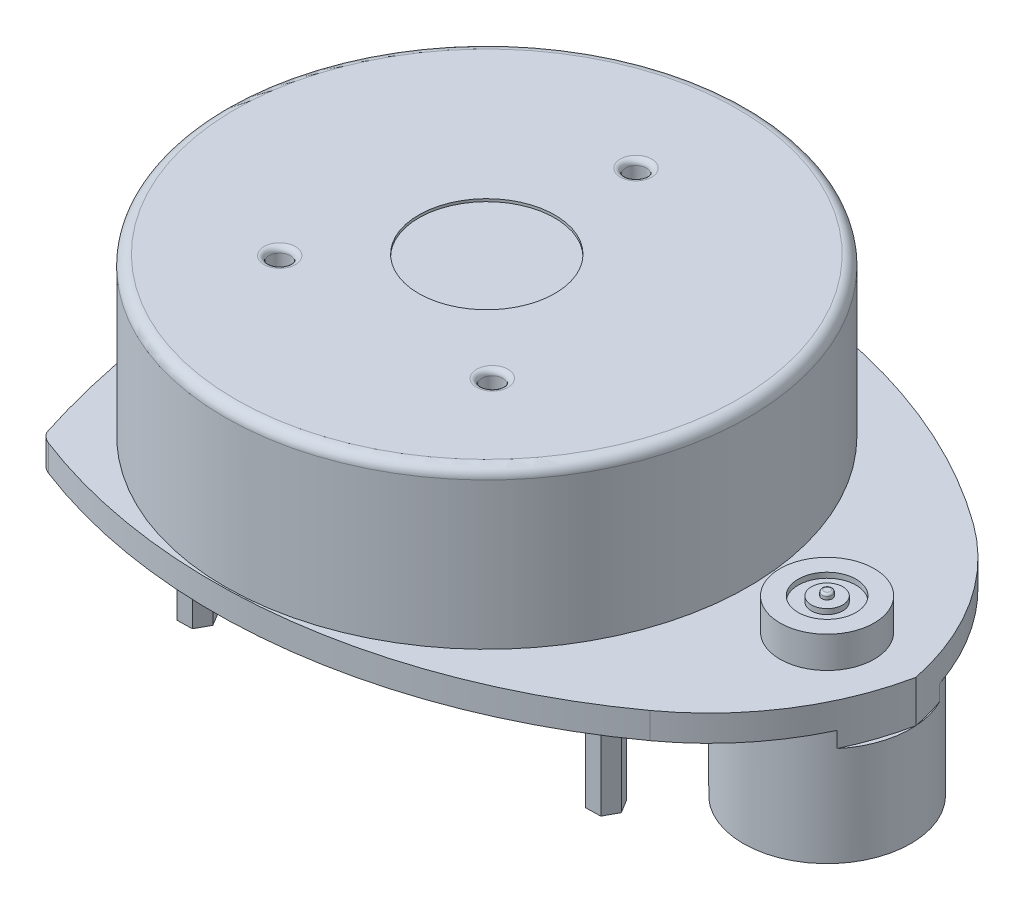
SolidWorks part; units mm, degrees
ref_plane "Спереди" through (0, 0, 0) normal (0, 0, 1) x (1, 0, 0)
ref_plane "Сверху" through (0, 0, 0) normal (0, 1, 0) x (1, 0, 0)
ref_plane "Справа" through (0, 0, 0) normal (1, 0, 0) x (0, 0, -1)
sketch "Эскиз1" plane through (0, 0, 0) normal (0, 1, 0) x (1, 0, 0)
  line L1 (-65, 55) -> (65, 55)
  line L2 (-65, 55) -> (-65, -55)
  line L3 (-65, -55) -> (65, -55)
  line L4 (65, 55) -> (65, -55)
  line L5 (-65, 55) -> (65, -55) construction
  line L6 (-65, -55) -> (65, 55) construction
  point P0 (0, 0)
  dimension "D1" = 130
  dimension "D2" = 110
extrude "Бобышка-Вытянуть1" add sketch "Эскиз1" along normal blind 5
sketch "Эскиз2" plane through (0, 5, 0) normal (0, 1, 0) x (1, 0, 0)
  line L0 (-65, 55) -> (-65, -55) construction
  circle A0 centre (-15, 0) radius 50
  point P2 (-65, 0)
  point P3 (-65, 0)
  dimension "D1" = 100
extrude "Бобышка-Вытянуть2" add sketch "Эскиз2" along normal blind 30
sketch "Эскиз3" plane through (0, 35, 0) normal (0, 1, 0) x (1, 0, 0)
  line L0 (-15, 0) -> (-15, 50000) construction
  line L1 (-14.25, -20) -> (-26.2883, -20) construction
  line L2 (-65, -55) -> (65, -55) construction
  circle A0 centre (-15, 28.5) radius 2
  circle A1 centre (-34.5539, -20) radius 2
  circle A2 centre (6.0539, -20) radius 2
  circle A3 centre (-15, 0) radius 50 construction
  circle A4 centre (-15, 0) radius 50 construction
  dimension "D2" = 4
  dimension "D3" = 35
  dimension "D4" = 27.9706
  dimension "D5" = 29.0391
extrude "Вырез-Вытянуть1" cut sketch "Эскиз3" against normal blind 5
fillet "Скругление1" radius 2 1 edges at (-15, 35, 50)
fillet "Скругление2" radius 1 3 edges at (6.0539, 35, 22) (-34.5539, 35, 22) (-15, 35, -26.5)
sketch "Эскиз4" plane through (0, 35, 0) normal (0, 1, 0) x (1, 0, 0)
  circle A0 centre (-15, 0) radius 13
  dimension "D1" = 26
extrude "Вырез-Вытянуть3" cut sketch "Эскиз4" against normal blind 0.5
sketch "Эскиз5" plane through (0, 5, 0) normal (0, 1, 0) x (1, 0, 0)
  line L0 (-42.2616, 30.7255) -> (-42.2616, -39.5827) construction
  line L1 (27.7384, 26.9972) -> (27.7384, -49973.0028) construction
  line L2 (-49.25, 0) -> (49950.75, 0) construction
  circle A0 centre (-15, 0) radius 48 construction
  circle A1 centre (-42.2616, 28) radius 1.25
  circle A2 centre (27.7384, 20) radius 1.25
  circle A3 centre (27.7384, -20) radius 1.25
  circle A4 centre (-42.2616, -28) radius 1.25
  point P4 (-14.2616, 47.9943)
  dimension "D1" = 28
  dimension "D3" = 2.5
  dimension "D2" = 42
  dimension "D4" = 28
  dimension "D5" = 20
extrude "Вырез-Вытянуть4" cut sketch "Эскиз5" against normal blind 5
sketch "Эскиз6" plane through (0, 5, 0) normal (0, 1, 0) x (1, 0, 0)
  line L0 (49.25, 0) -> (50049.25, 0) construction
  line L1 (65, -55) -> (65, 55) construction
  circle A0 centre (50, 0) radius 9
  circle A1 centre (-15, 0) radius 50 construction
  point P4 (65, 0)
  dimension "D1" = 18
  dimension "D2" = 65
extrude "Бобышка-Вытянуть3" add sketch "Эскиз6" along normal blind 7
sketch "Эскиз7" plane through (0, 12, 0) normal (0, 1, 0) x (1, 0, 0)
  circle A0 centre (50, 0) radius 9
  circle A1 centre (50, 0) radius 0.9935
extrude "Вырез-Вытянуть5" cut sketch "Эскиз7" against normal blind 1
sketch "Эскиз8" plane through (0, 11, 0) normal (0, 1, 0) x (1, 0, 0)
  circle A0 centre (50, 0) radius 3.0011
  circle A1 centre (50, 0) radius 5.5217
extrude "Вырез-Вытянуть6" cut sketch "Эскиз8" against normal blind 1
fillet "Скругление3" radius 0.4 1 edges at (50, 12, 0.9935)
sketch "Эскиз9" plane through (0, 5, 0) normal (0, 1, 0) x (1, 0, 0)
  circle A0 centre (50, 0) radius 16
  dimension "D1" = 32
extrude "Бобышка-Вытянуть4" add sketch "Эскиз9" against normal blind 27
sketch "Эскиз10" plane through (0, 0, 0) normal (0, -1, 0) x (1, 0, 0)
  line L0 (-49.25, 0) -> (49950.75, 0) construction
  line L1 (-40.8662, 25.4729) -> (-39.3754, 27.9449)
  line L2 (-39.3754, 27.9449) -> (-40.7708, 30.472)
  line L3 (-40.7708, 30.472) -> (-43.657, 30.5271)
  line L4 (-43.657, 30.5271) -> (-45.1479, 28.0551)
  line L5 (-45.1479, 28.0551) -> (-43.7525, 25.528)
  line L6 (-43.7525, 25.528) -> (-40.8662, 25.4729)
  line L7 (29.2455, 22.4621) -> (26.3597, 22.5363)
  line L8 (26.3597, 22.5363) -> (24.8526, 20.0742)
  line L9 (24.8526, 20.0742) -> (26.2312, 17.5379)
  line L10 (26.2312, 17.5379) -> (29.117, 17.4637)
  line L11 (29.117, 17.4637) -> (30.6242, 19.9258)
  line L12 (30.6242, 19.9258) -> (29.2455, 22.4621)
  line L13 (30.6242, -19.9258) -> (29.2455, -22.4621)
  line L14 (29.117, -17.4637) -> (30.6242, -19.9258)
  line L15 (26.2312, -17.5379) -> (29.117, -17.4637)
  line L16 (24.8526, -20.0742) -> (26.2312, -17.5379)
  line L17 (26.3597, -22.5363) -> (24.8526, -20.0742)
  line L18 (29.2455, -22.4621) -> (26.3597, -22.5363)
  line L19 (-43.7525, -25.528) -> (-40.8662, -25.4729)
  line L20 (-45.1479, -28.0551) -> (-43.7525, -25.528)
  line L21 (-43.657, -30.5271) -> (-45.1479, -28.0551)
  line L22 (-40.7708, -30.472) -> (-43.657, -30.5271)
  line L23 (-39.3754, -27.9449) -> (-40.7708, -30.472)
  line L24 (-40.8662, -25.4729) -> (-39.3754, -27.9449)
  circle A0 centre (-42.2616, 28) radius 2.5 construction
  circle A1 centre (27.7384, 20) radius 2.5 construction
  circle A2 centre (27.7384, -20) radius 2.5 construction
  circle A3 centre (-42.2616, -28) radius 2.5 construction
  point P17 (27.7384, 20)
  dimension "D1" = 5
  dimension "D2" = 5
extrude "Бобышка-Вытянуть5" add sketch "Эскиз10" along normal blind 24.6
sketch "Эскиз11" plane through (0, 5, 0) normal (0, 1, 0) x (1, 0, 0)
  circle A0 centre (-15, 0) radius 26
  dimension "D1" = 52
extrude "Бобышка-Вытянуть6" add sketch "Эскиз11" against normal blind 8
fillet "Скругление4" radius 1 1 edges at (-15, -3, 26)
sketch "Эскиз12" plane through (0, 5, 0) normal (0, 1, 0) x (1, 0, 0)
  line L0 (-65, 55) -> (-65, 0) construction
  line L1 (-65, -55) -> (65, -55) construction
  line L2 (-49.25, 1) -> (-50049.25, 1) construction
  line L4 (-56.096, 31.8881) -> (50.1555, 31.8881)
  line L5 (-56.096, 31.8881) -> (-56.096, -35.9274)
  line L6 (-56.096, -35.9274) -> (50.1555, -35.9274)
  line L7 (50.1555, 31.8881) -> (50.1555, -35.9274)
  arc A0 (-65, 1) -> (-57.5542, 43.501) centre (89.1094, -4.096) cw
  arc A2 (65, -5.5678) -> (65, 5.5678) centre (50, 0) ccw construction
  arc A3 (65.9687, 1) -> (46.0421, 31.8881) centre (16.2734, -9.188) ccw
  arc A5 (-55.6195, 45.088) -> (46.0421, 31.8881) centre (-16.9274, -55) cw
  arc A6 (-57.5542, 43.501) -> (-55.6195, 45.088) centre (-54.1772, 41.3571) cw
  arc A7 (-57.5542, -41.501) -> (-55.6195, -43.088) centre (-54.1772, -39.3571) ccw
  arc A8 (-55.6195, -43.088) -> (46.0421, -29.8881) centre (-16.9274, 57) ccw
  arc A9 (65.9687, 1) -> (46.0421, -29.8881) centre (16.2734, 11.188) cw
  arc A10 (-65, 1) -> (-57.5542, -41.501) centre (89.1094, 6.096) ccw
  circle M2 centre (-15, 0) radius 50
  line M3 (65, 55) -> (-65, 55)
  line M4 (-65, 55) -> (-65, 0)
  line M24 (-65, 0) -> (-65, -55)
  line M25 (-65, -55) -> (65, -55)
  line M26 (65, -55) -> (65, -5.5678)
  arc M27 (65, -5.5678) -> (65, 5.5678) centre (50, 0) ccw
  line M28 (65, 5.5678) -> (65, 55)
  dimension "D1" = 4
  dimension "D2" = 112
extrude "Вырез-Вытянуть7" cut sketch "Эскиз12" against normal blind 8 contours A0 A6 A5 L4 L7 A3 M27 M28 M3 M4 | A10 A9 L7 L6 A8 A7 M2 M24 M25 M26 M27 | L7 A9 A8 L6 | A3 L7 L4
scale "Ölçek1" bodies to scale 114 scale about centroid uniform scaling yes scale factor 0.05
